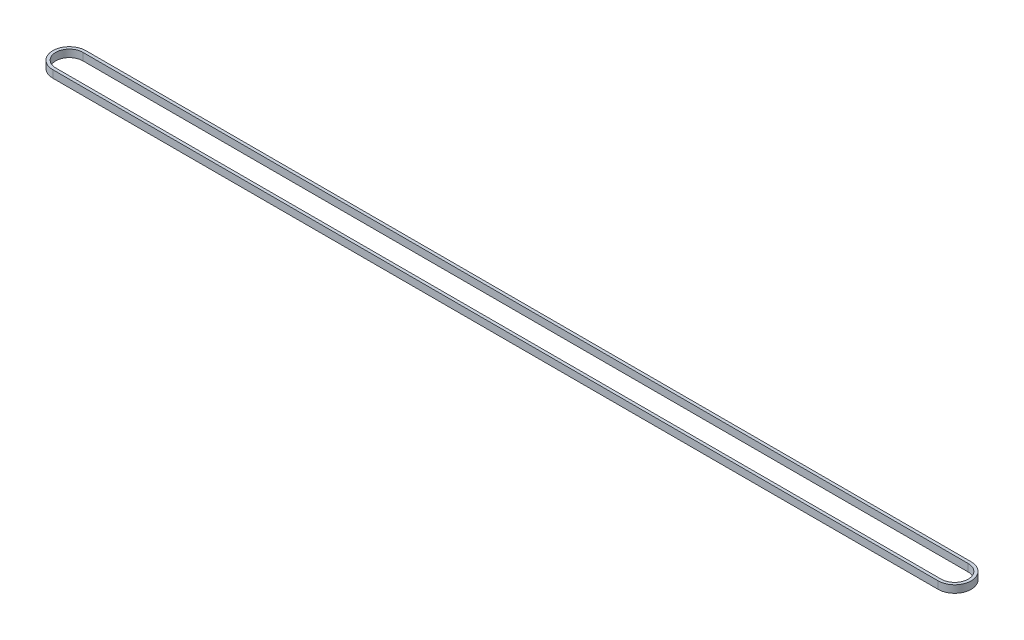
SolidWorks part; units mm, degrees
material "NEOPRENE"
ref_plane "Front Plane" through (0, 0, 0) normal (0, 0, 1) x (1, 0, 0)
ref_plane "Top Plane" through (0, 0, 0) normal (0, 1, 0) x (1, 0, 0)
ref_plane "Right Plane" through (0, 0, 0) normal (1, 0, 0) x (0, 0, -1)
sketch "Sketch1" plane through (0, 0, 0) normal (0, 1, 0) x (1, 0, 0)
  line L0 (298.855, 0) -> (-298.855, 0) construction
  line L1 (298.855, -9.15) -> (-298.855, -9.15)
  line L2 (298.855, 9.15) -> (-298.855, 9.15)
  line L3 (-298.855, 0) -> (298.855, 0) construction
  line L4 (-298.855, 11.15) -> (298.855, 11.15)
  line L5 (-298.855, -11.15) -> (298.855, -11.15)
  arc A0 (298.855, -9.15) -> (298.855, 9.15) centre (298.855, 0) ccw
  arc A1 (-298.855, 9.15) -> (-298.855, -9.15) centre (-298.855, 0) ccw
  arc A2 (-298.855, 11.15) -> (-298.855, -11.15) centre (-298.855, 0) ccw
  arc A3 (298.855, -11.15) -> (298.855, 11.15) centre (298.855, 0) ccw
  point P2 (0, 0)
  point P10 (0, 0)
  dimension "D2" = 9.15
  dimension "D1" = 597.71
  dimension "D3" = 2
extrude "Boss-Extrude1" add sketch "Sketch1" along normal blind 5
sketch "Sketch3" plane through (0, 5, 0) normal (0, 1, 0) x (1, 0, 0)
  arc A0 (-298.855, 11.15) -> (-298.855, -11.15) centre (-298.855, 0) ccw construction
  point P0 (-310.005, 0)
ref_plane "Plane1" through (-310.005, 5, 0) normal (-1, 0, 0) x (0, 0, 1)
sketch "Sketch4" plane through (-310.005, 5, 0) normal (-1, 0, 0) x (0, 0, 1)
  line L0 (0, 0) -> (0, -5)
  line L1 (11.15, 0) -> (-11.15, 0) construction
